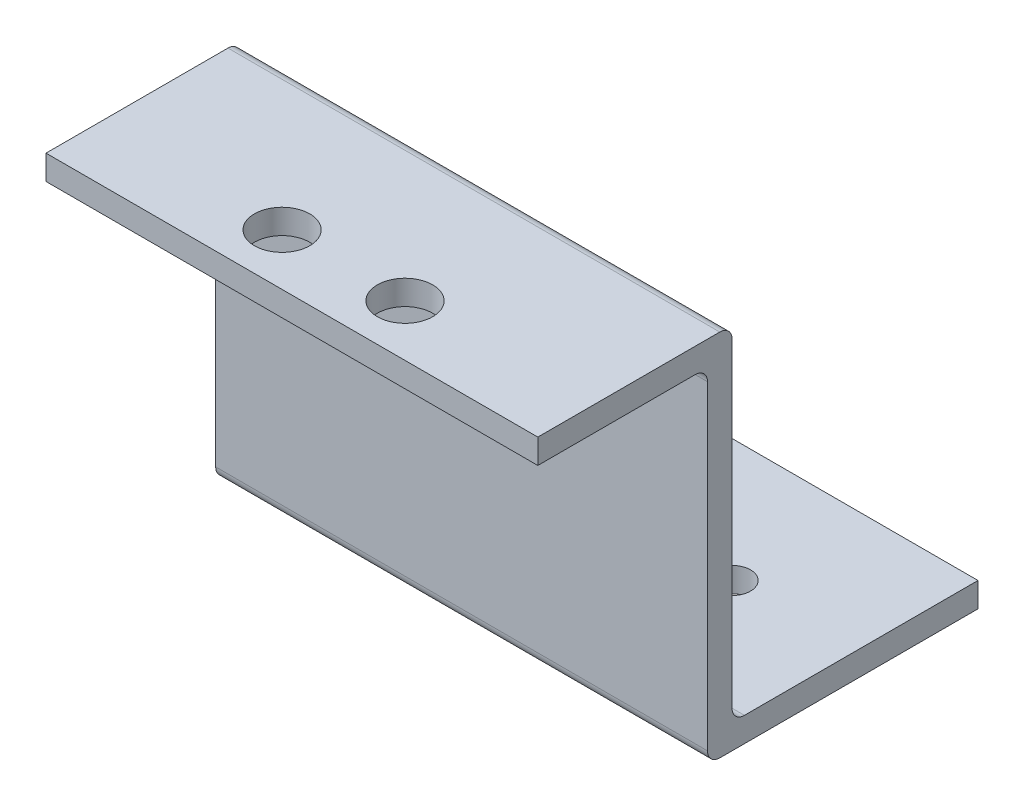
SolidWorks part; units mm, degrees
ref_plane "Front Plane" through (0, 0, 0) normal (0, 0, 1) x (1, 0, 0)
ref_plane "Top Plane" through (0, 0, 0) normal (0, 1, 0) x (1, 0, 0)
ref_plane "Right Plane" through (0, 0, 0) normal (1, 0, 0) x (0, 0, -1)
sketch "Sketch1" plane through (0, 0, 0) normal (0, 1, 0) x (1, 0, 0)
  line L0 (0.736, 26.632) -> (1.236, 26.632)
  line L1 (0.736, 26.632) -> (0.736, 19.832)
  line L2 (0.736, 19.832) -> (1.236, 19.832)
  line L3 (1.236, 26.632) -> (1.236, 19.832)
  line L4 (0.736, 26.632) -> (0.236, 26.632)
  line L5 (0.736, 26.632) -> (0.736, 19.832)
  line L6 (0.736, 19.832) -> (0.236, 19.832)
  line L7 (0.236, 26.632) -> (0.236, 19.832)
  line L8 (0.736, 19.832) -> (10.736, 19.832)
  line L9 (0.736, 19.832) -> (0.736, -20.568)
  line L10 (0.736, -20.568) -> (10.736, -20.568)
  line L11 (10.736, 19.832) -> (10.736, -20.568)
  line L12 (0.736, 19.832) -> (-9.264, 19.832)
  line L13 (0.736, 19.832) -> (0.736, -20.568)
  line L14 (0.736, -20.568) -> (-9.264, -20.568)
  line L15 (-9.264, 19.832) -> (-9.264, -20.568)
  line L16 (0.736, -20.568) -> (1.236, -20.568)
  line L17 (0.736, -20.568) -> (0.736, -27.368)
  line L18 (0.736, -27.368) -> (1.236, -27.368)
  line L19 (1.236, -20.568) -> (1.236, -27.368)
  line L20 (0.736, -20.568) -> (0.236, -20.568)
  line L21 (0.736, -20.568) -> (0.736, -27.368)
  line L22 (0.736, -27.368) -> (0.236, -27.368)
  line L23 (0.236, -20.568) -> (0.236, -27.368)
  line L25 (-19.264, 49.632) -> (20.736, 49.632)
  line L26 (-19.264, 49.632) -> (-19.264, -50.368)
  line L27 (-19.264, -50.368) -> (20.736, -50.368)
  line L28 (20.736, 49.632) -> (20.736, -50.368)
  circle A0 centre (-4.264, 24.032) radius 2.25
  circle A1 centre (5.736, 24.032) radius 2.25
  circle A2 centre (5.736, -24.768) radius 2.25
  circle A3 centre (-4.264, -24.768) radius 2.25
  circle A4 centre (-9.264, 39.632) radius 1.5
  circle A5 centre (10.736, 39.632) radius 1.5
  circle A6 centre (10.736, -40.368) radius 1.5
  circle A7 centre (-9.264, -40.368) radius 1.5
  dimension "D24" = 10
  dimension "D26" = 10
  dimension "D27" = 10
  dimension "D28" = 10
  dimension "D29" = 10
  dimension "D30" = 10
  dimension "D31" = 10
  dimension "D1" = 0.5
  dimension "D2" = 0.5
  dimension "D3" = 6.8
  dimension "D4" = 40.4
  dimension "D5" = 10
  dimension "D6" = 10
  dimension "D7" = 4.5
  dimension "D8" = 4.2
  dimension "D9" = 4.5
  dimension "D10" = 4.2
  dimension "D11" = 0.5
  dimension "D12" = 0.5
  dimension "D13" = 6.8
  dimension "D14" = 4.2
  dimension "D15" = 4.5
  dimension "D16" = 4.5
  dimension "D17" = 4.2
  dimension "D18" = 100
  dimension "D19" = 40
  dimension "D20" = 23
  dimension "D21" = 23
  dimension "D22" = 10
  dimension "D23" = 10
  dimension "D25" = 10
extrude "Boss-Extrude1" add sketch "Sketch1" along normal blind 2 contours L28 L25 L26 L27 A7 A6 A5 A4 A3 A2 A1 A0 L23 L14 L15 L12 L7 L4 L0 L3 L8 L11 L10 L19 L18 L22
sketch "Sketch2" plane through (0, 2, 0) normal (0, 1, 0) x (1, 0, 0)
  line L0 (20.736, 49.632) -> (20.736, -50.368) construction
  line L1 (-19.264, 49.632) -> (20.736, 49.632)
  line L2 (-19.264, 49.632) -> (-19.264, 33.632)
  line L3 (-19.264, 33.632) -> (20.736, 33.632)
  line L4 (20.736, 49.632) -> (20.736, 33.632)
  line L6 (-19.264, -50.368) -> (20.736, -50.368)
  line L7 (-19.264, -50.368) -> (-19.264, -34.368)
  line L8 (-19.264, -34.368) -> (20.736, -34.368)
  line L9 (20.736, -50.368) -> (20.736, -34.368)
  dimension "D1" = 40
  dimension "D2" = 16
  dimension "D3" = 40
  dimension "D4" = 16
extrude "Cut-Extrude1" cut sketch "Sketch2" against normal blind 10
sketch "Sketch4" plane through (0, 2, 0) normal (0, 1, 0) x (1, 0, 0)
  line L1 (-19.264, -34.368) -> (20.736, -34.368)
  line L2 (-19.264, -34.368) -> (-19.264, -36.368)
  line L3 (-19.264, -36.368) -> (20.736, -36.368)
  line L4 (20.736, -34.368) -> (20.736, -36.368)
  line L5 (20.736, 33.632) -> (-19.264, 33.632)
  line L6 (20.736, 33.632) -> (20.736, 35.632)
  line L7 (20.736, 35.632) -> (-19.264, 35.632)
  line L8 (-19.264, 33.632) -> (-19.264, 35.632)
  dimension "D1" = 2
  dimension "D2" = 40
  dimension "D3" = 40
  dimension "D4" = 2
extrude "Boss-Extrude2" add sketch "Sketch4" against normal blind 30
sketch "Sketch5" plane through (0, 0, -35.632) normal (0, 0, -1) x (-1, 0, 0)
  line L0 (19.264, -28) -> (19.264, 2) construction
  line L1 (-20.736, -28) -> (19.264, -28)
  line L2 (-20.736, -28) -> (-20.736, -26)
  line L3 (-20.736, -26) -> (19.264, -26)
  line L4 (19.264, -28) -> (19.264, -26)
  dimension "D1" = 2
  dimension "D2" = 40
extrude "Boss-Extrude3" add sketch "Sketch5" along normal blind 20
sketch "Sketch6" plane through (0, 0, 36.368) normal (0, 0, 1) x (1, 0, 0)
  line L0 (20.736, -28) -> (20.736, 2) construction
  line L1 (-19.264, -28) -> (20.736, -28)
  line L2 (-19.264, -28) -> (-19.264, -26)
  line L3 (-19.264, -26) -> (20.736, -26)
  line L4 (20.736, -28) -> (20.736, -26)
  dimension "D1" = 40
  dimension "D2" = 2
extrude "Boss-Extrude4" add sketch "Sketch6" along normal blind 20
fillet "Fillet1" radius 1 8 edges at (0.736, -28, -33.632) (0.736, -26, -35.632) (0.736, 2, -35.632) (0.736, 0, -33.632) (0.736, 0, 34.368) (0.736, -26, 36.368) (0.736, 2, 36.368) (0.736, -28, 34.368)
sketch "Sketch7" plane through (0, -26, 0) normal (0, 1, 0) x (1, 0, 0)
  line L0 (20.736, 55.632) -> (20.736, 36.632) construction
  line L1 (-19.264, 55.632) -> (20.736, 55.632) construction
  line L2 (-19.264, 55.632) -> (-19.264, 36.632) construction
  circle A0 centre (-9.264, 45.632) radius 1.5
  circle A1 centre (10.736, 45.632) radius 1.5
  dimension "D1" = 3
  dimension "D2" = 3
  dimension "D3" = 10
  dimension "D4" = 10
  dimension "D5" = 10
  dimension "D6" = 10
extrude "Cut-Extrude2" cut sketch "Sketch7" against normal blind 20
sketch "Sketch8" plane through (0, -26, 0) normal (0, 1, 0) x (1, 0, 0)
  line L0 (20.736, -56.368) -> (20.736, -37.368) construction
  line L1 (20.736, -56.368) -> (-19.264, -56.368) construction
  line L2 (-19.264, -56.368) -> (-19.264, -37.368) construction
  circle A0 centre (10.736, -46.368) radius 1.5
  circle A1 centre (-9.264, -46.368) radius 1.5
  dimension "D1" = 10
  dimension "D2" = 10
  dimension "D3" = 10
  dimension "D4" = 10
extrude "Cut-Extrude3" cut sketch "Sketch8" against normal blind 20
sketch "Sketch9" plane through (0, 2, 0) normal (0, 1, 0) x (1, 0, 0)
  line L1 (10.736, 19.832) -> (36.675, 19.832)
  line L2 (10.736, 19.832) -> (10.736, -106.8663)
  line L3 (10.736, -106.8663) -> (36.675, -106.8663)
  line L4 (36.675, 19.832) -> (36.675, -106.8663)
  line L5 (10.736, 19.832) -> (-32.318, 19.832)
  line L6 (10.736, 19.832) -> (10.736, -99.3118)
  line L7 (10.736, -99.3118) -> (-32.318, -99.3118)
  line L8 (-32.318, 19.832) -> (-32.318, -99.3118)
  line M1 (20.736, -35.368) -> (20.736, 34.632)
  line M3 (-19.264, 34.632) -> (-19.264, -35.368)
  line M4 (-19.264, -35.368) -> (20.736, -35.368)
  circle M5 centre (-4.264, -24.768) radius 2.25
  circle M6 centre (5.736, -24.768) radius 2.25
  line M9 (0.236, -27.368) -> (0.236, -20.568)
  line M10 (0.236, -20.568) -> (-9.264, -20.568)
  line M11 (-9.264, -20.568) -> (-9.264, 19.832)
  line M12 (-9.264, 19.832) -> (0.236, 19.832)
  line M16 (1.236, 19.832) -> (10.736, 19.832)
  line M17 (10.736, 19.832) -> (10.736, -20.568)
  line M18 (10.736, -20.568) -> (1.236, -20.568)
  line M19 (1.236, -20.568) -> (1.236, -27.368)
  line M20 (1.236, -27.368) -> (0.236, -27.368)
extrude "Cut-Extrude4" cut sketch "Sketch9" against normal through all contours L4 L1 L2 L3 M1 M4 | L5 M16 M12 M11 M10 M9 M20 M19 M18 M17 | L5 L2 M11 M3 M4 M18 M19 M20 M9 M10 M6 M5 | L2 L1 M17 M4 M1 | L5 L8 L7 L2 M4 M3
sketch "Sketch10" plane through (0, 2, 0) normal (0, 1, 0) x (1, 0, 0)
  line L1 (0.236, 26.632) -> (1.236, 26.632)
  line L2 (0.236, 26.632) -> (0.236, 19.832)
  line L3 (0.236, 19.832) -> (1.236, 19.832)
  line L4 (1.236, 26.632) -> (1.236, 19.832)
extrude "Boss-Extrude5" add sketch "Sketch10" against normal blind 2
sketch "Sketch11" plane through (-19.264, 0, 0) normal (-1, 0, 0) x (0, 0, 1)
  line L0 (-35.632, -25) -> (-35.632, 1) construction
  line L1 (-35.632, -16) -> (-45.632, -16)
  line L2 (-35.632, -16) -> (-35.632, -26)
  line L3 (-35.632, -26) -> (-45.632, -26)
  line L4 (-45.632, -16) -> (-45.632, -26)
  line L5 (-55.632, -26) -> (-36.632, -26) construction
  line L6 (-35.632, -16) -> (-45.632, -26)
  circle A0 centre (-36.632, -25) radius 1
  line M4 (-35.632, 1) -> (-35.632, -25)
  arc M5 (-35.632, -25) -> (-36.632, -26) centre (-36.632, -25) cw
  line M6 (-36.632, -26) -> (-55.632, -26)
  dimension "D1" = 10
  dimension "D2" = 10
extrude "Boss-Extrude6" add sketch "Sketch11" against normal blind 2 contours A0 L6 M4 M6 | A0 M5
